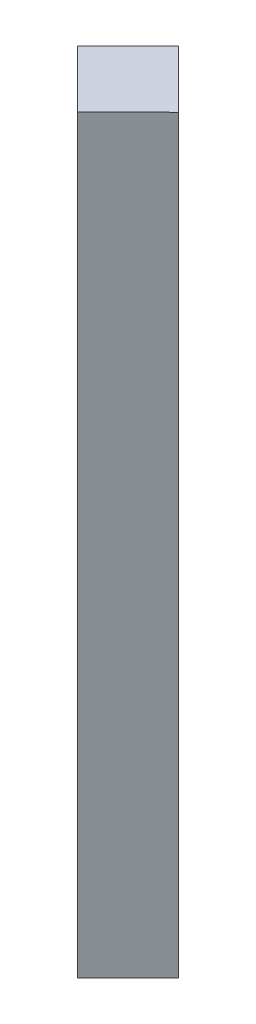
SolidWorks part; units mm, degrees
ref_plane "Front Plane" through (0, 0, 0) normal (0, 0, 1) x (1, 0, 0)
ref_plane "Top Plane" through (0, 0, 0) normal (0, 1, 0) x (1, 0, 0)
ref_plane "Right Plane" through (0, 0, 0) normal (1, 0, 0) x (0, 0, -1)
sketch "Sketch1" plane through (0, 0, 0) normal (0, 1, 0) x (1, 0, 0)
  line L0 (3.0048, -0.183) -> (0.1705, -3.0056) construction
  line L1 (3.0048, -0.183) -> (-0.1705, 3.0056) construction
  line L2 (0.1705, -3.0056) -> (-3.0048, 0.183) construction
  line L3 (-0.1705, 3.0056) -> (-3.0048, 0.183) construction
  line L4 (3.0048, -0.183) -> (-3.0048, 0.183) construction
  line L5 (0.1705, -3.0056) -> (-0.1705, 3.0056) construction
  line L6 (0.1708, -2.8641) -> (-2.8634, 0.1827)
  line L7 (-0.1708, 2.8641) -> (-2.8634, 0.1827)
  line L8 (2.8634, -0.1827) -> (-0.1708, 2.8641)
  line L9 (2.8634, -0.1827) -> (0.1708, -2.8641)
  point P0 (-2.2933, 0.4696)
  point P1 (0, 0)
  dimension "D1" = 0.1
extrude "Boss-Extrude1" add sketch "Sketch1" against normal offset from surface 8 and the other way offset from surface (30.3 mm away) 2
ref_plane "Plane1" through (0, 0, 0) normal (-0.7086, 0, 0.7056) x (0.7056, 0, 0.7086)
sketch "Sketch2" plane through (0, 0, 0) normal (-0.7086, 0, 0.7056) x (0.7056, 0, 0.7086)
  line L0 (0, 22) -> (0, 20.2) construction
  line L1 (0, 20.2) -> (0, -9.5)
  line L2 (2.15, -9.5) -> (-2.15, -9.5) construction
  line L3 (-1.8, 22) -> (-2.25, 22)
  line L4 (-1.8, 22) -> (0, 22) construction
  arc A0 (-1.8, 22) -> (0, 20.2) centre (-1.8, 20.2) cw
  point P2 (-1.1393, 2.6222)
  point P3 (-2.25, 3)
  dimension "D1" = 1.8
sketch "Sketch4" plane through (0, -9.5, 0) normal (0, -1, 0) x (1, 0, 0)
  circle A0 centre (0, 0) radius 0.8
sweep "Cut-Sweep1" cut profiles "Sketch4" path "Sketch2"
